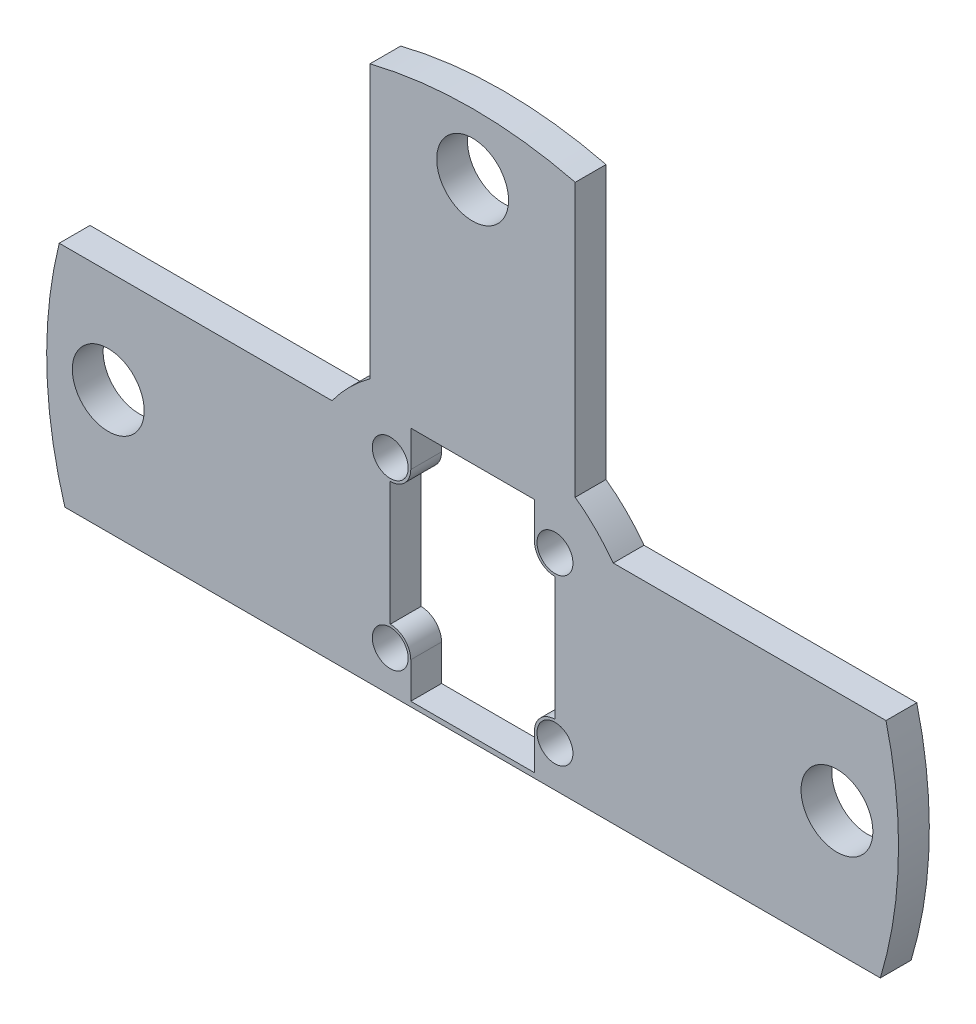
SolidWorks part; units mm, degrees
ref_plane "Alzado" through (0, 0, 0) normal (0, 0, 1) x (1, 0, 0)
ref_plane "Planta" through (0, 0, 0) normal (0, 1, 0) x (1, 0, 0)
ref_plane "Vista lateral" through (0, 0, 0) normal (1, 0, 0) x (0, 0, -1)
sketch "Croquis1" plane through (0, 0, 0) normal (0, 0, 1) x (1, 0, 0)
  line L0 (-39.7272, -12) -> (-26.949, -12)
  line L1 (26.949, -12) -> (39.7272, -12)
  arc A0 (33.4103, -12) -> (-33.4103, -12) centre (0, 0) ccw construction
  circle A1 centre (-35.5, 0) radius 3.5
  circle A2 centre (0, 35.5) radius 3.5
  circle A3 centre (35.5, 0) radius 3.5
  arc A4 (39.7272, -12) -> (-39.7272, -12) centre (0, 0) ccw
  arc A5 (26.949, -12) -> (-26.949, -12) centre (0, 0) ccw
  dimension "D1" = 71
  dimension "D2" = 7
  dimension "D3" = 7
  dimension "D4" = 7
  dimension "D5" = 83
  dimension "D6" = 6
  dimension "D7" = 12
extrude "Saliente-Extruir1" add sketch "Croquis1" along normal blind 52.5
sketch "Croquis2" plane through (0, 0, 52.5) normal (0, 0, 1) x (1, 0, 0)
  line L1 (8.025, -8.025) -> (-8.025, -8.025) construction
  line L2 (8.025, -8.025) -> (8.025, 8.025) construction
  line L3 (8.025, 8.025) -> (-8.025, 8.025) construction
  line L4 (-8.025, -8.025) -> (-8.025, 8.025) construction
  line L5 (8.025, -8.025) -> (-8.025, 8.025) construction
  line L6 (8.025, 8.025) -> (-8.025, -8.025) construction
  circle A0 centre (-8.025, 8.025) radius 1.75
  circle A1 centre (8.025, 8.025) radius 1.75
  circle A2 centre (-8.025, -8.025) radius 1.75
  circle A3 centre (8.025, -8.025) radius 1.75
  circle A4 centre (0, 0) radius 29.5
  point P0 (0, 0)
  dimension "D3" = 3.5
  dimension "D4" = 3.5
  dimension "D5" = 3.5
  dimension "D6" = 3.5
  dimension "D1" = 16.05
  dimension "D2" = 16.05
extrude "Saliente-Extruir2" add sketch "Croquis2" against normal blind 3
sketch "Croquis3" plane through (0, 0, 52.5) normal (0, 0, 1) x (1, 0, 0)
  line L0 (-8.025, 6.025) -> (-8.025, -6.025)
  line L1 (-6.025, -8.025) -> (6.025, -8.025)
  line L2 (8.025, -6.025) -> (8.025, 6.025)
  line L3 (-6.025, 8.025) -> (6.025, 8.025)
  arc A0 (-8.025, 6.025) -> (-6.025, 8.025) centre (-8.025, 8.025) ccw
  arc A1 (6.025, 8.025) -> (8.025, 6.025) centre (8.025, 8.025) ccw
  arc A2 (-6.025, -8.025) -> (-8.025, -6.025) centre (-8.025, -8.025) ccw
  arc A3 (8.025, -6.025) -> (6.025, -8.025) centre (8.025, -8.025) ccw
  dimension "D1" = 4
  dimension "D2" = 4
  dimension "D3" = 4
  dimension "D4" = 4
extrude "Cortar-Extruir1" cut sketch "Croquis3" against normal through all
sketch "Croquis4" plane through (0, 0, 52.5) normal (0, 0, 1) x (1, 0, 0)
  line L0 (-8.025, -9.775) -> (-19.0736, -9.775) construction
  circle A0 centre (-8.025, -8.025) radius 1.75 construction
sketch "Croquis5" plane through (0, 0, 52.5) normal (0, 0, 1) x (1, 0, 0)
  line L0 (-26.949, -12) -> (26.949, -12)
  line L1 (26.949, -12) -> (26.949, -33.1583)
  line L2 (26.949, -33.1583) -> (-29.2908, -29.7307)
  line L3 (-29.2908, -29.7307) -> (-26.949, -12)
extrude "Cortar-Extruir2" cut sketch "Croquis5" against normal through all
sketch "Croquis6" plane through (0, 0, 52.5) normal (0, 0, 1) x (1, 0, 0)
  line L0 (-40.2772, 10) -> (-13.6988, 10)
  line L1 (-39.7272, -12) -> (39.7272, -12) construction
  line L2 (-10, 13.6988) -> (-10, 40.2772)
  line L3 (0, 0) -> (0, -22.1241) construction
  line L4 (10, 13.6988) -> (10, 40.2772)
  line L5 (40.2772, 10) -> (13.6988, 10)
  arc A0 (13.6988, 10) -> (10, 13.6988) centre (0, 0) ccw
  arc A1 (39.7272, -12) -> (-39.7272, -12) centre (0, 0) ccw construction
  circle A2 centre (-35.5, 0) radius 3.5 construction
  circle A3 centre (0, 35.5) radius 3.5 construction
  arc A4 (40.2772, 10) -> (10, 40.2772) centre (0, 0) ccw
  arc A5 (-10, 40.2772) -> (-40.2772, 10) centre (0, 0) ccw
  arc A6 (-10, 13.6988) -> (-13.6988, 10) centre (0, 0) ccw
  point P1 (-13.6988, 15)
  dimension "D2" = 10
  dimension "D1" = 0
  dimension "D3" = 10
  dimension "D4" = 0
extrude "Cortar-Extruir3" cut sketch "Croquis6" against normal through all
sketch "Croquis7" plane through (0, 0, 52.5) normal (0, 0, 1) x (1, 0, 0)
  line L0 (-6.025, 8.025) -> (-6.025, 11.525)
  line L1 (-6.025, 11.525) -> (6.025, 11.525)
  line L2 (6.025, 11.525) -> (6.025, 8.025)
  line L3 (-6.025, 8.025) -> (6.025, 8.025)
  line L4 (0, 0) -> (0, -4.4023) construction
  line L5 (0, 0) -> (4.6009, 0) construction
  line L6 (-6.025, -8.025) -> (-6.025, -11.525)
  line L7 (-6.025, -11.525) -> (6.025, -11.525)
  line L8 (6.025, -11.525) -> (6.025, -8.025)
  line L9 (-6.025, -8.025) -> (6.025, -8.025)
  dimension "D1" = 3.5
extrude "Cortar-Extruir4" cut sketch "Croquis7" against normal through all
sketch "Croquis8" plane through (0, 0, 0) normal (0, 0, -1) x (-1, 0, 0)
  line L1 (49.4469, -43.8269) -> (-49.4469, -43.8269)
  line L2 (49.4469, -43.8269) -> (49.4469, 43.8269)
  line L3 (49.4469, 43.8269) -> (-49.4469, 43.8269)
  line L4 (-49.4469, -43.8269) -> (-49.4469, 43.8269)
  line L5 (49.4469, -43.8269) -> (-49.4469, 43.8269) construction
  line L6 (49.4469, 43.8269) -> (-49.4469, -43.8269) construction
  point P0 (0, 0)
extrude "Cortar-Extruir5" cut sketch "Croquis8" against normal up to surface (49.5 mm away) up to face at (0, 0, 49.5)
